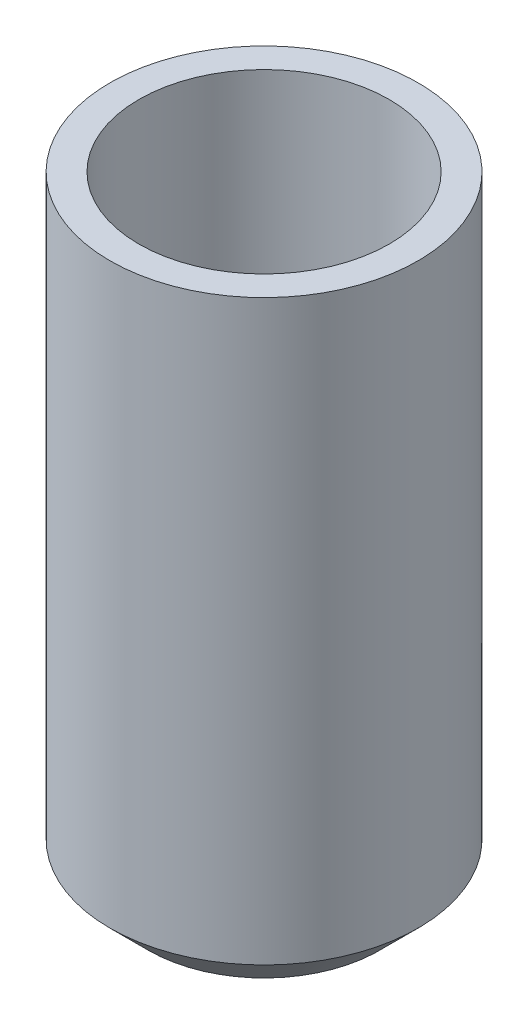
SolidWorks part; units mm, degrees
ref_plane "Front Plane" through (0, 0, 0) normal (0, 0, 1) x (1, 0, 0)
ref_plane "Top Plane" through (0, 0, 0) normal (0, 1, 0) x (1, 0, 0)
ref_plane "Right Plane" through (0, 0, 0) normal (1, 0, 0) x (0, 0, -1)
sketch "Sketch2" plane through (0, 0, 0) normal (1, 0, 0) x (0, 0, -1)
  line L0 (0, 0) -> (6, 0)
  line L1 (8, 2) -> (8, 32)
  line L2 (6, 0) -> (8, 2)
  line L3 (2.6501, 1.5) -> (5.3787, 1.5) construction
  line L4 (5.3787, 1.5) -> (6.5, 2.6213)
  line L5 (6.5, 2.6213) -> (6.5, 32) construction
  line L6 (0, 2.0607) -> (5.9393, 2.0607) construction
  line L7 (0, 1.5) -> (5.3787, 1.5) construction
  line L8 (6.5, 12.0607) -> (5.3787, 6.5)
  line L9 (5.3787, 6.5) -> (6.5, 6.5)
  line L10 (5.9393, 6.5) -> (5.9393, 2.0607) construction
  line L11 (0, 2.0607) -> (0, 0)
  line L12 (2.6501, 1.5) -> (5.3787, 1.5)
  line L13 (6.5, 2.6213) -> (6.5, 6.5)
  line L14 (6.5, 12.0607) -> (6.5, 32)
  line L15 (6.5, 32) -> (8, 32)
  arc A0 (0, 2.0607) -> (2.6501, 1.5) centre (0, -4.4831) cw
  point P1 (8, 0)
  dimension "D1" = 8
  dimension "D2" = 32
  dimension "D4" = 10
  dimension "D6" = 5
  dimension "D3" = 1.5
revolve "Revolve1" add sketch "Sketch2" angle 360 about L11
